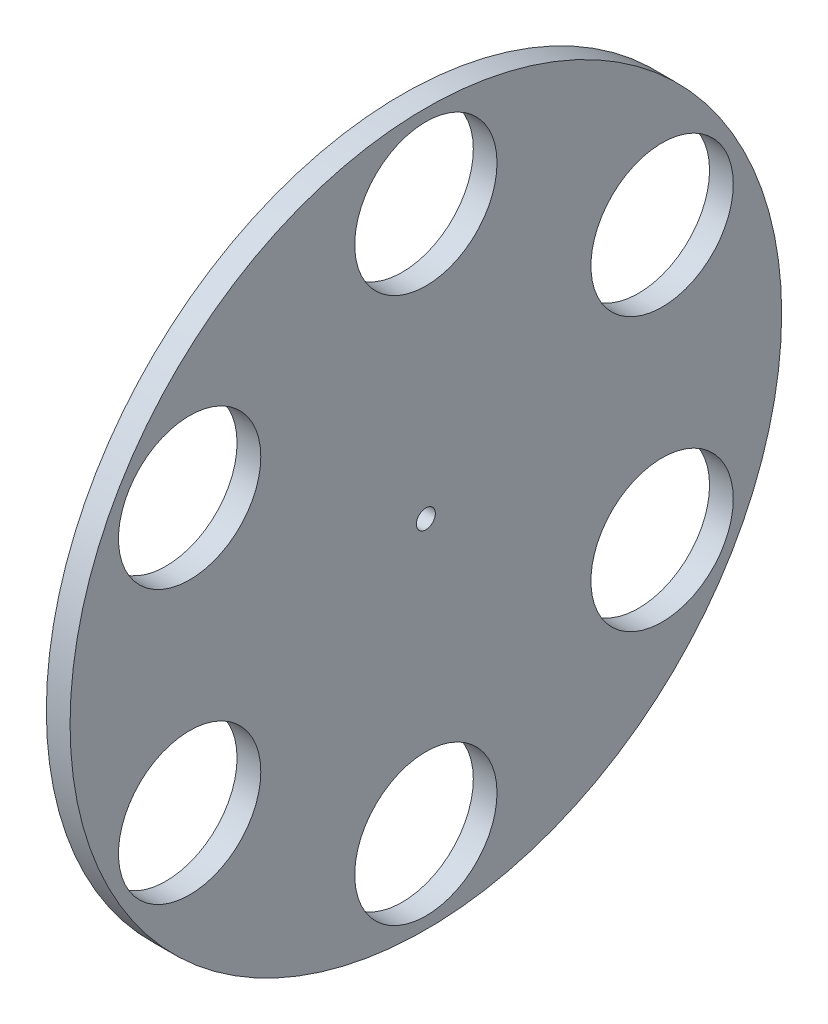
SolidWorks part; units mm, degrees
ref_plane "Front Plane" through (0, 0, 0) normal (0, 0, 1) x (1, 0, 0)
ref_plane "Top Plane" through (0, 0, 0) normal (0, 1, 0) x (1, 0, 0)
ref_plane "Right Plane" through (0, 0, 0) normal (1, 0, 0) x (0, 0, -1)
sketch "Sketch1" plane through (0, 0, 0) normal (1, 0, 0) x (0, 0, -1)
  line L0 (0, 0) -> (0, 150) construction
  line L1 (0, 0) -> (129.9038, 75) construction
  line L2 (0, 0) -> (129.9038, -75) construction
  line L3 (0, 0) -> (0, -150) construction
  line L4 (0, 0) -> (-129.9038, -75) construction
  line L5 (0, 0) -> (-129.9038, 75) construction
  circle A0 centre (0, 0) radius 150
  circle A1 centre (0, 0) radius 4
  circle A2 centre (0, 115) radius 30
  circle A3 centre (99.5929, 57.5) radius 30
  circle A4 centre (99.5929, -57.5) radius 30
  circle A5 centre (0, -115) radius 30
  circle A6 centre (-99.5929, -57.5) radius 30
  circle A7 centre (-99.5929, 57.5) radius 30
  point P13 (0, 0)
  point P26 (0, 0)
  dimension "D1" = 300
  dimension "D2" = 8
  dimension "D4" = 60
  dimension "D5" = 115
  dimension "D3" = 6
  dimension "D6" = 6
extrude "Boss-Extrude1" add sketch "Sketch1" along normal blind 10
ref_plane "Plane1" through (10, 0, 0) normal (-1, 0, 0) x (0, 0, 1)
